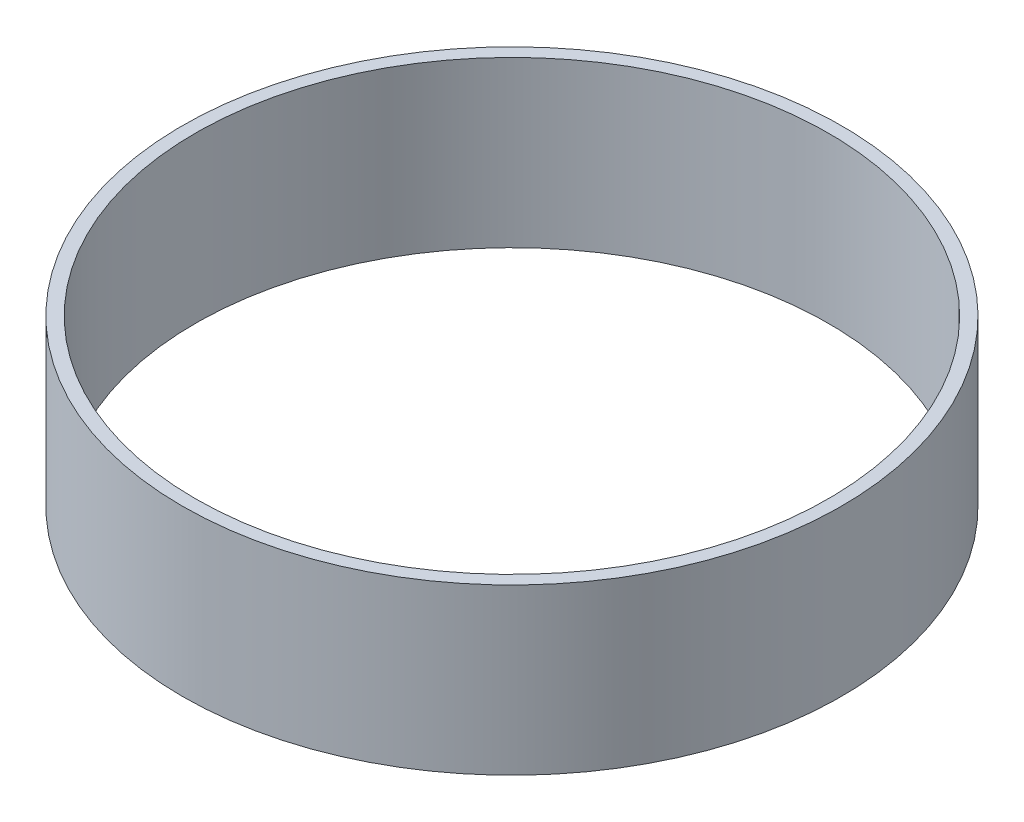
SolidWorks part; units mm, degrees
ref_plane "Front Plane" through (0, 0, 0) normal (0, 0, 1) x (1, 0, 0)
ref_plane "Top Plane" through (0, 0, 0) normal (0, 1, 0) x (1, 0, 0)
ref_plane "Right Plane" through (0, 0, 0) normal (1, 0, 0) x (0, 0, -1)
sketch "Sketch1" plane through (0, 0, 0) normal (0, 1, 0) x (1, 0, 0)
  circle A0 centre (0, 0) radius 25.4
  circle A1 centre (0, 0) radius 24.4
  dimension "D1" = 50.8
  dimension "D2" = 1
extrude "Boss-Extrude1" add sketch "Sketch1" along normal blind 12.7
